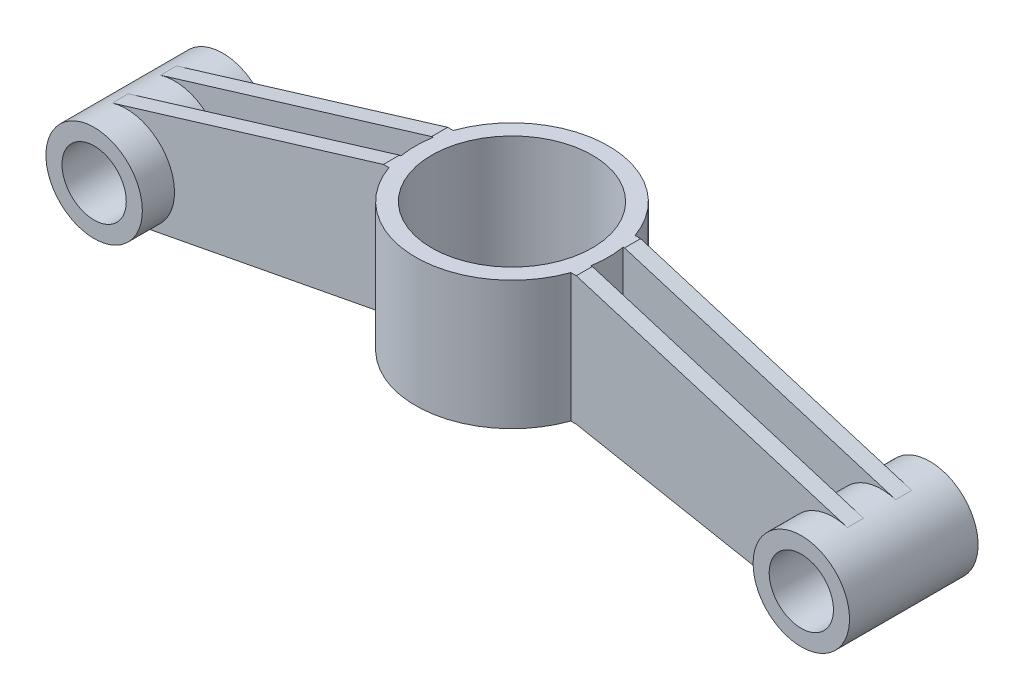
SolidWorks part; units mm, degrees
ref_plane "Front Plane" through (0, 0, 0) normal (0, 0, 1) x (1, 0, 0)
ref_plane "Top Plane" through (0, 0, 0) normal (0, 1, 0) x (1, 0, 0)
ref_plane "Right Plane" through (0, 0, 0) normal (1, 0, 0) x (0, 0, -1)
sketch "Sketch1" plane through (0, 0, 0) normal (0, 1, 0) x (1, 0, 0)
  circle A0 centre (0, 0) radius 30
  circle A1 centre (0, 0) radius 25
  dimension "D1" = 60
  dimension "D2" = 50
extrude "Boss-Extrude1" add sketch "Sketch1" along normal blind 40
sketch "Sketch4" plane through (0, 0, 0) normal (0, 0, 1) x (1, 0, 0)
  line L0 (25, 40) -> (-25, 40) construction
  line L1 (0, -30.25) -> (0, 30.25) construction
  circle A0 centre (-110, 0) radius 15
  circle A1 centre (-110, 0) radius 10
  circle A2 centre (110, 0) radius 10
  circle A3 centre (110, 0) radius 15
  point P3 (-110, -16.5395)
  dimension "D1" = 30
  dimension "D2" = 20
  dimension "D3" = 110
  dimension "D4" = 40
extrude "Boss-Extrude2" add sketch "Sketch4" along normal mid plane 40 separate body
sketch "Sketch5" plane through (0, 0, 0) normal (0, 0, 1) x (1, 0, 0)
  line L0 (-114.3632, 14.3514) -> (-30, 40)
  line L2 (-30, 0) -> (-107.1875, -14.734)
  line L3 (-30, 40) -> (-25, 40)
  line L4 (0, -30.25) -> (0, 30.25) construction
  line L5 (30, 0) -> (107.1875, -14.734)
  line L6 (114.3632, 14.3514) -> (30, 40)
  line L8 (30, 40) -> (-30, 40) construction
  line L9 (-25, 40) -> (-25, 0)
  line L10 (-30, 0) -> (30, 0) construction
  line L11 (-25, 0) -> (-30, 0)
  line L12 (25, 0) -> (30, 0)
  line L13 (25, 40) -> (25, 0)
  line L14 (30, 40) -> (25, 40)
  circle A0 centre (-110, 0) radius 15 construction
  arc A1 (-107.1875, -14.734) -> (-114.3632, 14.3514) centre (-110, 0) ccw
  circle A4 centre (110, 0) radius 15 construction
  arc A5 (114.3632, 14.3514) -> (107.1875, -14.734) centre (110, 0) ccw
  point P23 (-28.1748, 42.5027)
  point P25 (0, 0)
  point P26 (-31.501, -2.1634)
  dimension "D1" = 50
extrude "Boss-Extrude3" add sketch "Sketch5" along normal blind 5 from offset 5
mirror "Mirror2" about plane through (0, 0, 0) normal (0, 0, 1) of "Boss-Extrude3"
